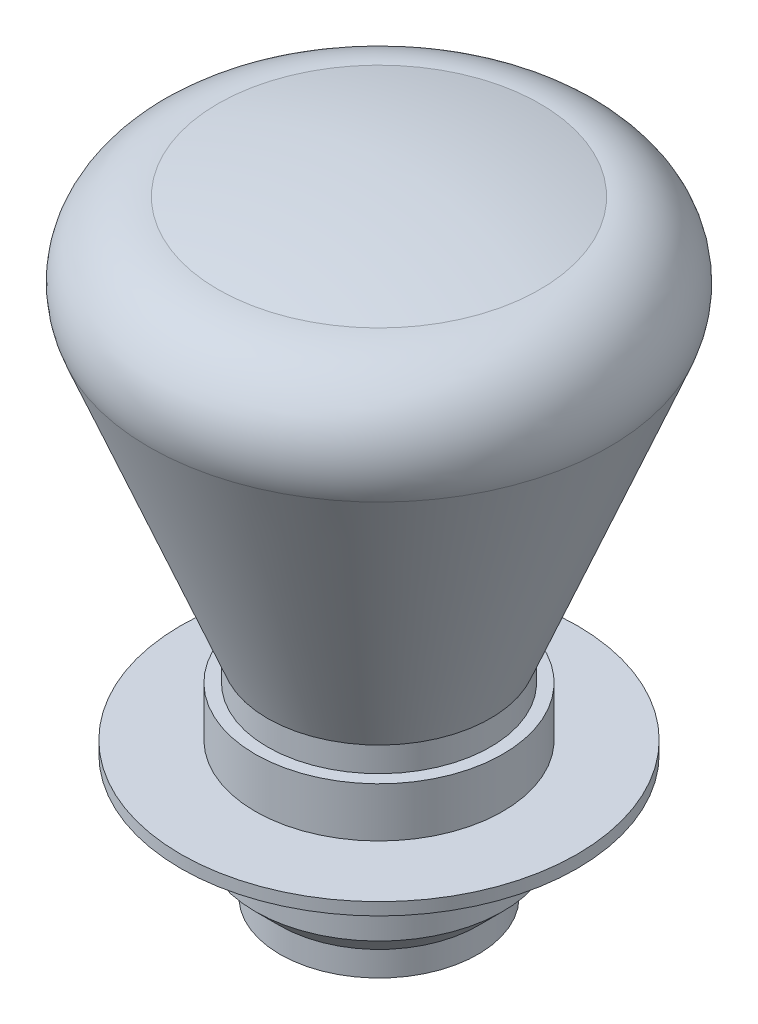
SolidWorks part; units mm, degrees
ref_plane "Front Plane" through (0, 0, 0) normal (0, 0, 1) x (1, 0, 0)
ref_plane "Top Plane" through (0, 0, 0) normal (0, 1, 0) x (1, 0, 0)
ref_plane "Right Plane" through (0, 0, 0) normal (1, 0, 0) x (0, 0, -1)
sketch "Sketch1" plane through (0, 0, 0) normal (0, 0, 1) x (1, 0, 0)
  line L0 (0, 89.3404) -> (0, -113.296) construction
  line L1 (0, -33.262) -> (-4, -33.262)
  line L2 (-4, -33.262) -> (-4, -32.262)
  line L3 (-4, -32.262) -> (-5, -31.262)
  line L4 (-5, -31.262) -> (-5, -28.262)
  line L5 (-5, -28.262) -> (-8, -28.262)
  line L6 (-8, -28.262) -> (-8, -27.762)
  line L7 (-8, -27.762) -> (-5, -27.762)
  line L8 (-5, -27.762) -> (-5, -25.762)
  line L9 (-5, -25.762) -> (-4.5, -25.762)
  line L10 (-4.5, -25.762) -> (-4.5, -24.762)
  line L11 (-4.5, -24.762) -> (-9.2829, -12.8825)
  line L12 (-6.5, -8.762) -> (0, -8.762)
  arc A0 (-6.5, -8.762) -> (-9.2829, -12.8825) centre (-6.5, -11.762) ccw
  arc A3 (-6.5, -8.762) -> (0, -7.9982) centre (0, -36.0382) cw
  point P19 (0, -8.762)
  point P20 (-5, -26.762)
  dimension "D1" = 3
  dimension "D12" = 5
  dimension "D14" = 28.04
  dimension "D2" = 1
  dimension "D3" = 1
  dimension "D4" = 1
  dimension "D5" = 3
  dimension "D6" = 0.5
  dimension "D7" = 2
  dimension "D8" = 1
  dimension "D9" = 0.5
  dimension "D10" = 3
  dimension "D11" = 2
  dimension "D13" = 16
revolve "Revolve1" add sketch "Sketch1" angle 360 about L0
